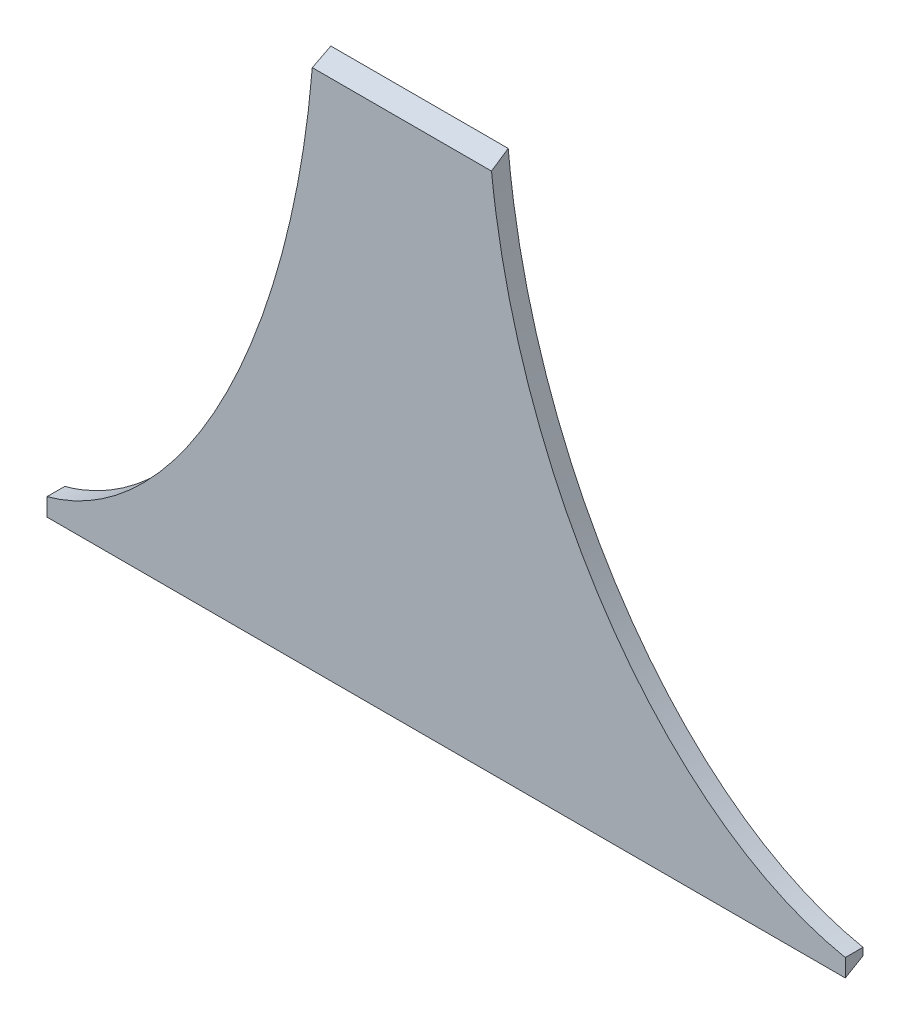
SolidWorks part; units mm, degrees
ref_plane "Front Plane" through (0, 0, 0) normal (0, 0, 1) x (1, 0, 0)
ref_plane "Top Plane" through (0, 0, 0) normal (0, 1, 0) x (1, 0, 0)
ref_plane "Right Plane" through (0, 0, 0) normal (1, 0, 0) x (0, 0, -1)
sketch "Sketch1" plane through (0, 0, 0) normal (0, 0, 1) x (1, 0, 0)
  line L0 (0, 0) -> (-114.3, 0)
  line L1 (-114.3, 0) -> (-114.3, 2.54)
  line L2 (-50.8, 76.2) -> (-76.2, 76.2)
  line L3 (0, 2.54) -> (0, 0)
  ellipse E0 centre (-114.3, 76.2) end of major axis (-121.5068, 1.9117) minor radius 37.9681 (-114.3, 2.54) -> (-76.2, 76.2) ccw
  ellipse E1 centre (0, 76.2) end of major axis (12.7938, 2.3506) minor radius 50.3928 (-50.8, 76.2) -> (0, 2.54) ccw
  dimension "D2" = 76.2
  dimension "D1" = 50.8
  dimension "D3" = 25.4
  dimension "D4" = 114.3
  dimension "D5" = 2.54
  dimension "D6" = 2.54
  dimension "D7" = 76.2
  dimension "D8" = 76.2
extrude "Boss-Extrude1" add sketch "Sketch1" along normal blind 2.54
sketch "Sketch4" plane through (-114.3, 0, 0) normal (-1, 0, 0) x (0, 0, 1)
  line L0 (2.54, 0) -> (0, 1.4665)
  line L1 (0, 1.4665) -> (0, 0)
  line L2 (0, 0) -> (2.54, 0)
  line L3 (0, 2.54) -> (0, 0) construction
  dimension "D1" = 30
extrude "Cut-Extrude3" cut sketch "Sketch4" against normal up to next
sketch "Sketch5" plane through (-114.3, 0, 0) normal (-1, 0, 0) x (0, 0, 1)
  line L0 (0, 76.2) -> (2.54, 74.7335)
  line L1 (2.54, 74.7335) -> (2.54, 76.2)
  line L2 (2.54, 76.2) -> (0, 76.2)
  line L3 (2.54, 76.2) -> (0, 76.2) construction
  line L4 (2.54, 2.54) -> (2.54, 76.2) construction
  line L5 (0, 76.2) -> (0, 2.54) construction
  dimension "D1" = 30
extrude "Cut-Extrude4" cut sketch "Sketch5" against normal blind 77.978
